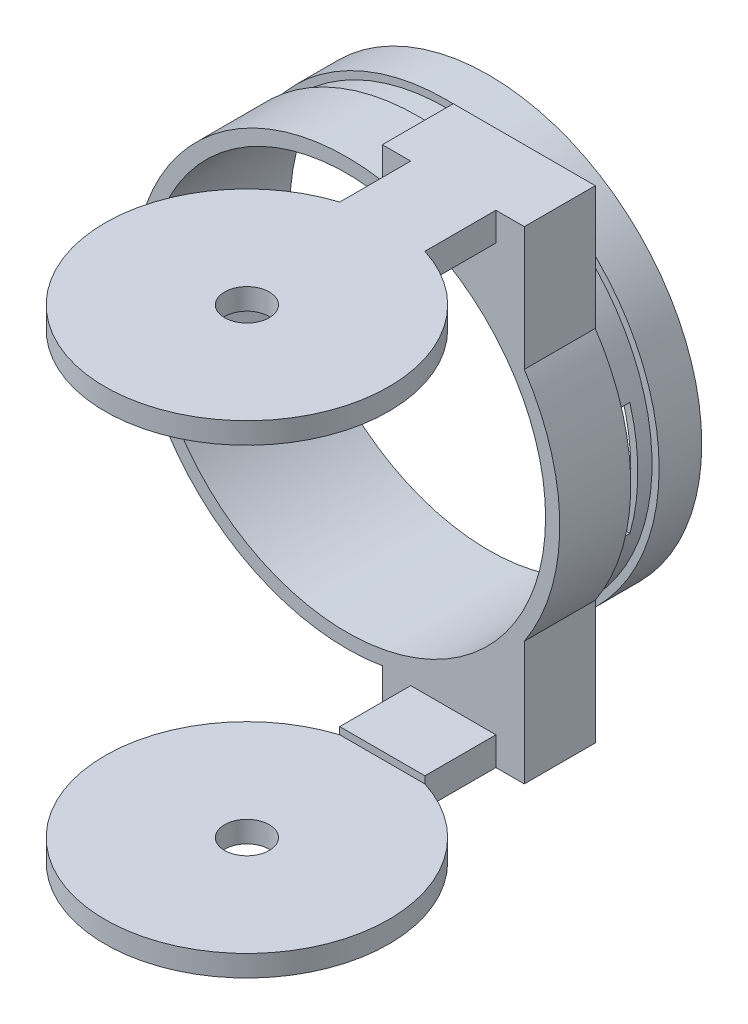
SolidWorks part; units mm, degrees
ref_plane "Front Plane" through (0, 0, 0) normal (0, 0, 1) x (1, 0, 0)
ref_plane "Top Plane" through (0, 0, 0) normal (0, 1, 0) x (1, 0, 0)
ref_plane "Right Plane" through (0, 0, 0) normal (1, 0, 0) x (0, 0, -1)
sketch "Sketch2" plane through (0, 0, 0) normal (0, 0, 1) x (1, 0, 0)
  circle A0 centre (0, 0) radius 38.1
  circle A1 centre (0, 0) radius 35.56
  dimension "D1" = 76.2
  dimension "D2" = 2.54
extrude "Boss-Extrude1" add sketch "Sketch2" along normal blind 12.7
sketch "Sketch4" plane through (0, 0, 12.7) normal (0, 0, 1) x (1, 0, 0)
  line L0 (6.985, 0) -> (-6.985, 0) construction
  line L1 (11.43, 43.18) -> (26.67, 43.18)
  line L2 (11.43, 43.18) -> (11.43, 38.1)
  line L3 (11.43, 38.1) -> (26.67, 38.1)
  line L4 (26.67, 43.18) -> (26.67, 38.1)
  line L5 (11.43, 43.18) -> (26.67, 38.1) construction
  line L6 (11.43, 38.1) -> (26.67, 43.18) construction
  line L7 (26.67, -43.18) -> (26.67, -38.1)
  line L8 (11.43, -43.18) -> (26.67, -43.18)
  line L9 (11.43, -43.18) -> (11.43, -38.1)
  line L10 (11.43, -38.1) -> (26.67, -38.1)
  point P0 (19.05, 40.64)
  dimension "D1" = 15.24
  dimension "D2" = 19.05
  dimension "D3" = 40.64
  dimension "D4" = 5.08
extrude "Boss-Extrude2" add sketch "Sketch4" along normal blind 12.7 separate body
sketch "Sketch5" plane through (0, 0, 12.7) normal (0, 0, -1) x (-1, 0, 0)
  line L0 (-11.43, -38.1) -> (-11.43, -43.18) construction
  line L1 (-31.75, 38.1) -> (-6.35, 38.1)
  line L2 (-31.75, 38.1) -> (-31.75, 43.18)
  line L3 (-31.75, 43.18) -> (-6.35, 43.18)
  line L4 (-6.35, 38.1) -> (-6.35, 43.18)
  line L5 (-31.75, -38.1) -> (-6.35, -38.1)
  line L6 (-31.75, -38.1) -> (-31.75, -43.18)
  line L7 (-31.75, -43.18) -> (-6.35, -43.18)
  line L8 (-6.35, -38.1) -> (-6.35, -43.18)
  line L9 (-11.43, 43.18) -> (-11.43, 38.1) construction
  line L10 (-11.43, 38.1) -> (-26.67, 38.1) construction
  line L11 (-26.67, -38.1) -> (-11.43, -38.1) construction
  point P8 (-6.35, -40.64)
  point P11 (-6.35, 40.64)
  dimension "D1" = 5.08
  dimension "D2" = 5.08
  dimension "D3" = 25.4
  dimension "D4" = 25.4
  dimension "D5" = 5.08
  dimension "D6" = 5.08
extrude "Boss-Extrude4" add sketch "Sketch5" along normal blind 12.7 separate body
sketch "Sketch6" plane through (0, -38.1, 0) normal (0, 1, 0) x (1, 0, 0)
  line L4 (6.35, -12.7) -> (31.75, -12.7)
  line L5 (31.75, -12.7) -> (31.75, 0)
  line L6 (31.75, 0) -> (6.35, 0)
  line L7 (6.35, 0) -> (6.35, -12.7)
  line L8 (6.35, -12.7) -> (31.75, -12.7)
  line L9 (31.75, -12.7) -> (31.75, 0)
  line L10 (31.75, 0) -> (6.35, 0)
  line L11 (6.35, 0) -> (6.35, -12.7)
  dimension "D1" = 0
extrude "Boss-Extrude5" add sketch "Sketch6" along normal up to surface (17.0394 mm away)
sketch "Sketch7" plane through (0, 38.1, 0) normal (0, -1, 0) x (1, 0, 0)
  line L4 (31.75, 12.7) -> (6.35, 12.7)
  line L5 (6.35, 12.7) -> (6.35, 0)
  line L6 (6.35, 0) -> (31.75, 0)
  line L7 (31.75, 0) -> (31.75, 12.7)
  line L8 (31.75, 12.7) -> (6.35, 12.7)
  line L9 (6.35, 12.7) -> (6.35, 0)
  line L10 (6.35, 0) -> (31.75, 0)
  line L11 (31.75, 0) -> (31.75, 12.7)
  dimension "D1" = 0
extrude "Boss-Extrude6" add sketch "Sketch7" along normal up to surface (0.5329 mm away)
sketch "Sketch8" plane through (0, 43.18, 0) normal (0, 1, 0) x (1, 0, 0)
  circle A0 centre (19.05, -49.6301) radius 25.4
  dimension "D1" = 50.8
extrude "Boss-Extrude7" add sketch "Sketch8" against normal blind 3.81
mirror "Mirror1" about plane through (0, 0, 0) normal (0, 1, 0) of "Boss-Extrude7"
sketch "Sketch9" plane through (0, 0, 0) normal (0, 0, -1) x (-1, 0, 0)
  circle A0 centre (0, 0) radius 35.56
  circle A1 centre (0, 0) radius 36.83
  dimension "D1" = 1.27
extrude "Boss-Extrude8" add sketch "Sketch9" along normal blind 5.08
sketch "Sketch10" plane through (0, 0, -5.08) normal (0, 0, -1) x (-1, 0, 0)
  circle A0 centre (0, 0) radius 38.1
  circle A1 centre (0, 0) radius 35.56
  dimension "D1" = 2.54
extrude "Boss-Extrude9" add sketch "Sketch10" along normal blind 7.62
sketch "Sketch13" plane through (0, 0, 0) normal (1, 0, 0) x (0, 0, -1)
  line L0 (0, -36.83) -> (0, 36.83) construction
  line L1 (0, 10.16) -> (2.54, 10.16)
  line L2 (0, 10.16) -> (0, -10.16)
  line L3 (0, -10.16) -> (2.54, -10.16)
  line L4 (2.54, 10.16) -> (2.54, -10.16)
  dimension "D1" = 20.32
  dimension "D2" = 2.54
  dimension "D3" = 10.16
extrude "Cut-Extrude2" cut sketch "Sketch13" along normal through all
sketch "Sketch14" plane through (0, 43.18, 0) normal (0, 1, 0) x (1, 0, 0)
  circle A0 centre (19.05, -49.6301) radius 4
  dimension "D1" = 8
extrude "Cut-Extrude3" cut sketch "Sketch14" against normal through all both and the other way through all
